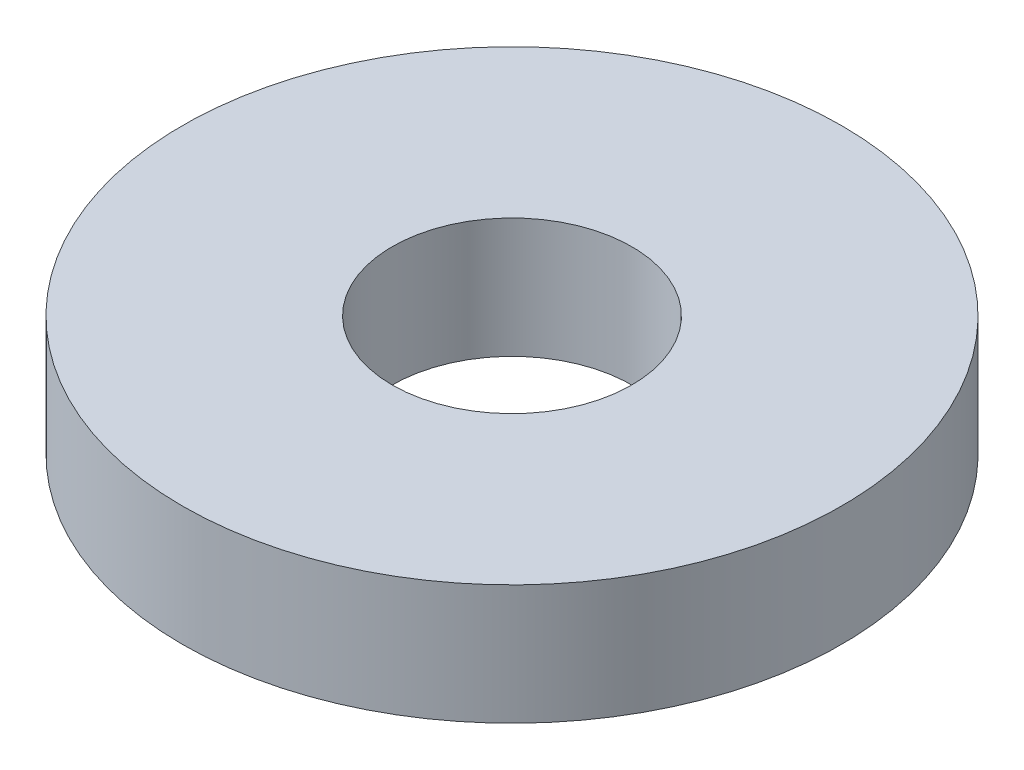
SolidWorks part; units mm, degrees
ref_plane "Alzado" through (0, 0, 0) normal (0, 0, 1) x (1, 0, 0)
ref_plane "Planta" through (0, 0, 0) normal (0, 1, 0) x (1, 0, 0)
ref_plane "Vista lateral" through (0, 0, 0) normal (1, 0, 0) x (0, 0, -1)
sketch "Croquis1" plane through (0, 0, 0) normal (0, 1, 0) x (1, 0, 0)
  circle A0 centre (0, 0) radius 11
  circle A1 centre (0, 0) radius 4
  dimension "D1" = 8
  dimension "D2" = 22
extrude "Saliente-Extruir1" add sketch "Croquis1" along normal blind 4
